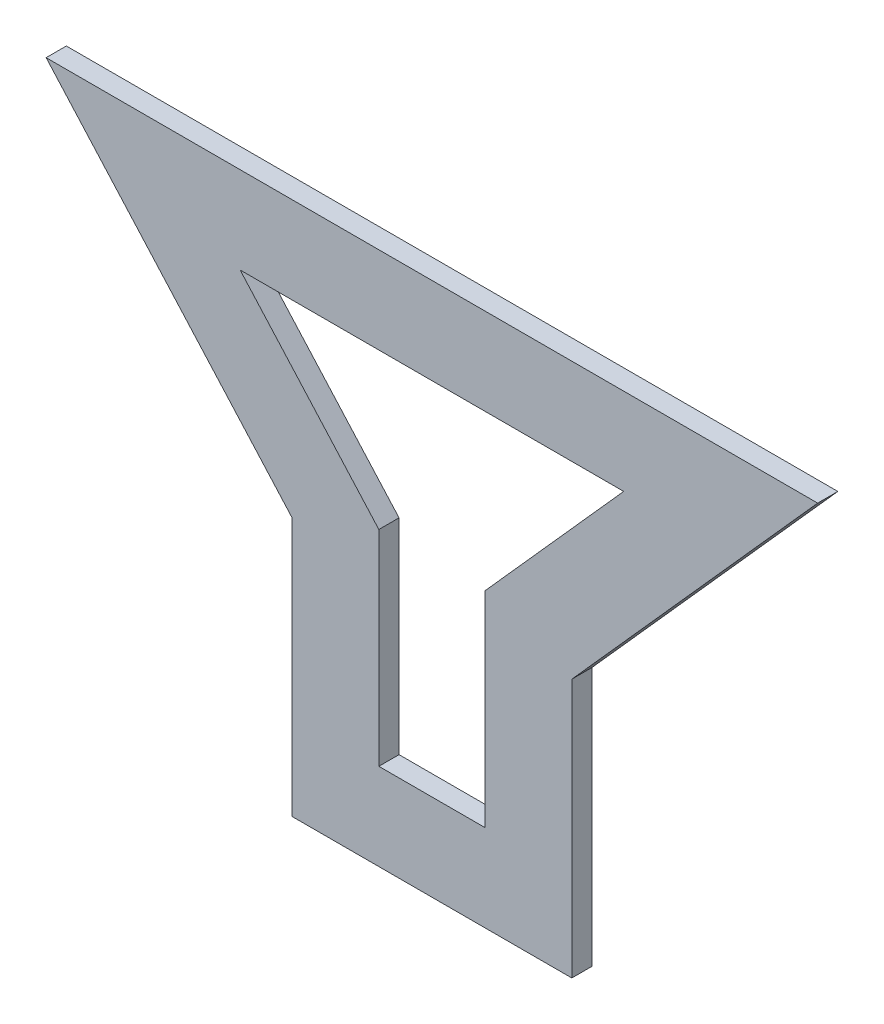
SolidWorks part; units mm, degrees
ref_plane "Спереди" through (0, 0, 0) normal (0, 0, 1) x (1, 0, 0)
ref_plane "Сверху" through (0, 0, 0) normal (0, 1, 0) x (1, 0, 0)
ref_plane "Справа" through (0, 0, 0) normal (1, 0, 0) x (0, 0, -1)
sketch "Эскиз5" plane through (0, 0, 0) normal (0, 0, 1) x (1, 0, 0)
  line L0 (0, -125.6018) -> (0, 84.5398) construction
  line L1 (69.2703, 2.5328) -> (69.2703, -125.6018)
  line L2 (69.2703, 2.5328) -> (190.9954, 138.8843)
  line L3 (190.9954, 138.8843) -> (-190.9954, 138.8843)
  line L4 (69.2703, -125.6018) -> (-69.2703, -125.6018)
  line L5 (-26.2703, -82.6018) -> (26.2703, -82.6018)
  line L6 (26.2703, -82.6018) -> (26.2703, 18.9341)
  line L7 (26.2703, 18.9341) -> (94.9661, 95.8843)
  line L8 (94.9661, 95.8843) -> (-94.9661, 95.8843)
  line L9 (-26.2703, 18.9341) -> (-94.9661, 95.8843)
  line L10 (-26.2703, -82.6018) -> (-26.2703, 18.9341)
  line L11 (-69.2703, 2.5328) -> (-190.9954, 138.8843)
  line L12 (-69.2703, 2.5328) -> (-69.2703, -125.6018)
  circle A0 centre (136.7614, 111.3834) radius 10 construction
  circle A1 centre (50, -10.9786) radius 10 construction
  circle A2 centre (50, -110.9786) radius 10 construction
  circle A3 centre (-50, -110.9786) radius 10 construction
  circle A4 centre (-50, -10.9786) radius 10 construction
  circle A5 centre (-136.7614, 111.3834) radius 10 construction
  point P10 (0, 0)
  point P19 (0, 0)
  point P20 (0, 0)
  point P21 (26.2703, 29.8191)
  point P22 (0, 0)
  point P23 (190.9954, 138.8843)
  point P24 (0, 0)
  point P25 (0, 0)
  point P33 (0, 95.8843)
  point P35 (0, -82.6018)
  point P37 (0, 138.8843)
  dimension "D1" = 20
  dimension "D5" = 43
  dimension "D2" = 50
  dimension "D3" = 100
  dimension "D4" = 150
  dimension "D6" = 43
  dimension "D7" = 43
  dimension "D8" = 43
extrude "Бобышка-Вытянуть2" add sketch "Эскиз5" along normal blind 10 contours L4 L12 L11 L3 L2 L1 | L8 L9 L10 L5 L6 L7
